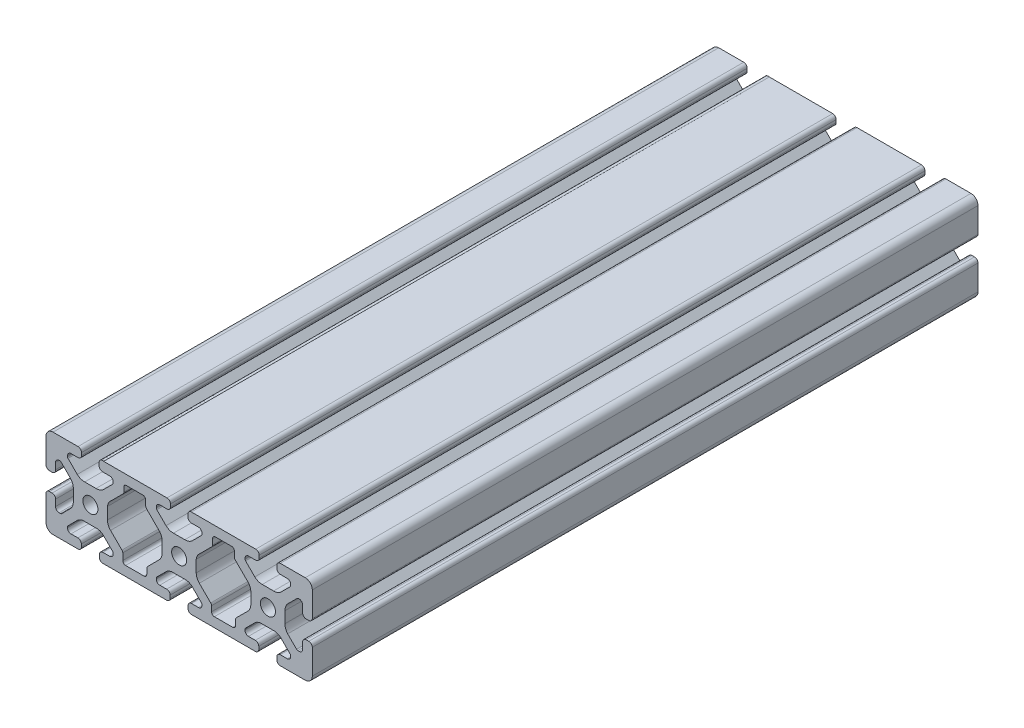
SolidWorks part; units mm, degrees
material "6105-T5 Aluminum"
ref_plane "Front Plane" through (0, 0, 0) normal (0, 0, 1) x (1, 0, 0)
ref_plane "Top Plane" through (0, 0, 0) normal (0, 1, 0) x (1, 0, 0)
ref_plane "Right Plane" through (0, 0, 0) normal (1, 0, 0) x (0, 0, -1)
sketch "Sketch1" plane through (0, 0, 0) normal (0, 0, 1) x (1, 0, 0)
  line L0 (-66.9907, 0) -> (65.4005, 0) construction
  line L128 (-34.0397, 20) -> (-5.4835, 20)
  line L129 (-36.0865, 17.2476) -> (-36.0865, 18.4276)
  line L130 (-31.285, 15.68) -> (-34.5165, 15.68)
  line L131 (-29.715, 13.6545) -> (-29.715, 14.11)
  line L132 (-16.3366, 15.68) -> (-23.6634, 15.68)
  line L133 (-24.9334, 14.9061) -> (-24.9334, 12.538)
  line L134 (-25.3054, 11.6399) -> (-30.5988, 6.3465)
  line L135 (-32.3, 3.2591) -> (-32.3, -2.0252)
  line L136 (-14.009, -20) -> (-21.7801, -20)
  line L137 (-19.7616, 20) -> (-19.7616, -25.1394) construction
  line L138 (-24.1394, -15.68) -> (-15.8606, -15.68)
  line L139 (-25.4094, -11.4093) -> (-25.4094, -14.41)
  line L140 (-30.9088, -5.384) -> (-25.7814, -10.5113)
  line L142 (-29.9376, 13.1171) -> (-34.0919, 8.9628)
  line L143 (-37.4506, 7.7) -> (-42.5494, 7.7)
  line L144 (-45.9081, 8.9628) -> (-50.0624, 13.1171)
  line L145 (-50.285, 13.6545) -> (-50.285, 14.11)
  line L146 (-48.715, 15.68) -> (-45.5696, 15.68)
  line L147 (-43.9996, 17.25) -> (-43.9996, 18.43)
  line L148 (-45.5696, 20) -> (-53, 20)
  line L149 (-53, 20) -> (-56.83, 20)
  line L150 (-60, 16.8406) -> (-60, 13.0106)
  line L151 (-60, 13.0106) -> (-60, 5.5825)
  line L152 (-58.3243, 4.1259) -> (-57.1443, 4.1259)
  line L153 (-55.68, 5.8839) -> (-55.68, 8.7865)
  line L154 (-54.11, 10.3565) -> (-53.726, 10.3565)
  line L155 (-53.1886, 10.1339) -> (-49.0111, 5.9564)
  line L156 (-47.7, 2.571) -> (-47.7, -2.502)
  line L157 (-48.9155, -5.8608) -> (-52.9291, -9.8744)
  line L158 (-53.4665, -10.097) -> (-54.111, -10.097)
  line L159 (-55.68, -8.4722) -> (-55.68, -5.5696)
  line L160 (-57.25, -3.9996) -> (-58.43, -3.9996)
  line L161 (-60, -5.5696) -> (-60, -13)
  line L162 (-60, -13) -> (-60, -16.83)
  line L163 (-57.0574, -20) -> (-53.2274, -20)
  line L164 (-53.2274, -20) -> (-45.797, -20)
  line L165 (-44.06, -18.4389) -> (-44.06, -17.25)
  line L166 (-45.63, -15.68) -> (-48.7404, -15.68)
  line L167 (-50.3104, -14.11) -> (-50.3104, -13.7197)
  line L168 (-50.0878, -13.1823) -> (-46.3105, -9.405)
  line L169 (-43.3425, -7.7407) -> (-36.6594, -7.7407)
  line L170 (-33.6914, -9.405) -> (-29.9611, -13.1353)
  line L171 (-29.7385, -13.6727) -> (-29.7385, -14.1108)
  line L172 (-31.2596, -15.68) -> (-34.37, -15.68)
  line L173 (-35.94, -17.25) -> (-35.94, -18.43)
  line L174 (-34.37, -20) -> (-25.991, -20)
  line L175 (-25.991, -20) -> (-21.7801, -20)
  line L176 (-5.63, -20) -> (-14.009, -20)
  line L177 (-4.06, -17.2093) -> (-4.06, -18.43)
  line L178 (-8.7404, -15.68) -> (-5.63, -15.68)
  line L179 (-10.3104, -13.7197) -> (-10.3104, -14.11)
  line L180 (-6.3105, -9.405) -> (-10.0878, -13.1823)
  line L181 (3.3406, -7.7407) -> (-3.3425, -7.7407)
  line L182 (29.9376, 13.1171) -> (34.0919, 8.9628)
  line L183 (3.9116, 17.25) -> (3.9116, 18.43)
  line L184 (8.715, 15.68) -> (5.4816, 15.68)
  line L185 (10.285, 13.6545) -> (10.285, 14.11)
  line L186 (15.0666, 14.2735) -> (15.0666, 11.9054)
  line L187 (14.6946, 11.0074) -> (9.4012, 5.7139)
  line L188 (7.7, 2.6265) -> (7.7, -2.6578)
  line L189 (14.5906, -12.0419) -> (14.5906, -14.41)
  line L190 (9.0912, -6.0165) -> (14.2186, -11.1439)
  line L191 (10.0624, 13.1171) -> (5.9081, 8.9628)
  line L192 (6.3086, -9.405) -> (10.037, -13.1334)
  line L193 (10.2596, -13.6708) -> (10.2596, -14.11)
  line L194 (8.6896, -15.68) -> (5.5792, -15.68)
  line L195 (4.0092, -17.2093) -> (4.0092, -18.43)
  line L196 (5.5792, -20) -> (13.9582, -20)
  line L197 (25.9402, -20) -> (21.7292, -20)
  line L198 (34.3192, -20) -> (25.9402, -20)
  line L199 (35.8892, -17.2093) -> (35.8892, -18.43)
  line L200 (31.2088, -15.68) -> (34.3192, -15.68)
  line L201 (29.6886, -13.6708) -> (29.6886, -14.0552)
  line L202 (33.6397, -9.405) -> (29.9112, -13.1334)
  line L203 (43.2907, -7.7407) -> (36.6076, -7.7407)
  line L204 (50.036, -13.1823) -> (46.2587, -9.405)
  line L205 (50.2586, -14.0552) -> (50.2586, -13.7197)
  line L206 (45.5792, -15.68) -> (48.6896, -15.68)
  line L207 (-2.5494, 7.7) -> (2.5494, 7.7)
  line L208 (-10.0624, 13.1171) -> (-5.9081, 8.9628)
  line L209 (-9.0912, -6.0165) -> (-14.2186, -11.1439)
  line L210 (-14.5906, -12.0419) -> (-14.5906, -14.41)
  line L211 (-7.7, 2.6265) -> (-7.7, -2.6578)
  line L212 (-14.6946, 11.1439) -> (-9.4012, 5.8505)
  line L213 (-15.0666, 14.41) -> (-15.0666, 12.0419)
  line L214 (-10.285, 13.6545) -> (-10.285, 14.11)
  line L215 (-8.715, 15.68) -> (-5.4835, 15.68)
  line L216 (-3.9135, 17.25) -> (-3.9135, 18.43)
  line L217 (-40, 24.8708) -> (-40, -18.43) construction
  line L218 (0, 29.4355) -> (0, -23.1087) construction
  line L219 (-23.0962, 16.9038) -> (-63.6857, -23.6857) construction
  line L220 (-56.2671, 16.2671) -> (-22.7875, -17.2125) construction
  line L221 (44.0092, -18.4389) -> (44.0092, -17.2093)
  line L222 (53.1766, -20) -> (45.7462, -20)
  line L223 (57.0066, -20) -> (53.1766, -20)
  line L224 (60, -13) -> (60, -16.83)
  line L225 (60, -5.5696) -> (60, -13)
  line L226 (57.25, -3.9996) -> (58.43, -3.9996)
  line L227 (55.68, -8.4722) -> (55.68, -5.5696)
  line L228 (53.4665, -10.097) -> (54.111, -10.097)
  line L229 (48.9155, -5.8608) -> (52.9291, -9.8744)
  line L230 (47.7, 2.571) -> (47.7, -2.502)
  line L231 (53.1886, 10.1339) -> (49.0111, 5.9564)
  line L232 (54.11, 10.3565) -> (53.726, 10.3565)
  line L233 (55.68, 5.8839) -> (55.68, 8.7865)
  line L234 (58.3243, 4.1259) -> (57.1443, 4.1259)
  line L235 (60, 13.0106) -> (60, 5.5825)
  line L236 (60, 16.8406) -> (60, 13.0106)
  line L237 (53, 20) -> (56.83, 20)
  line L238 (45.5696, 20) -> (53, 20)
  line L239 (43.9996, 17.25) -> (43.9996, 18.43)
  line L240 (48.715, 15.68) -> (45.5696, 15.68)
  line L241 (50.285, 13.6545) -> (50.285, 14.11)
  line L242 (45.9081, 8.9628) -> (50.0624, 13.1171)
  line L243 (37.4506, 7.7) -> (42.5494, 7.7)
  line L244 (30.9088, -6.0165) -> (25.7814, -11.1439)
  line L245 (25.4094, -12.0419) -> (25.4094, -14.41)
  line L246 (24.1394, -15.68) -> (15.8606, -15.68)
  line L247 (13.9582, -20) -> (21.7292, -20)
  line L248 (32.3, 2.6265) -> (32.3, -2.6578)
  line L249 (25.3054, 11.1439) -> (30.5988, 5.8505)
  line L250 (24.9334, 14.41) -> (24.9334, 12.0419)
  line L251 (16.3366, 15.68) -> (23.6634, 15.68)
  line L252 (29.715, 13.6545) -> (29.715, 14.11)
  line L253 (31.285, 15.68) -> (34.5165, 15.68)
  line L254 (36.0865, 17.25) -> (36.0865, 18.43)
  line L255 (34.5165, 20) -> (5.4816, 20)
  arc A111 (-36.0865, 18.4276) -> (-34.0397, 20) centre (-34.5184, 18.5048) cw
  circle A112 centre (-40, 0) radius 3.4
  arc A113 (-34.5165, 15.68) -> (-36.0865, 17.2476) centre (-34.5165, 17.25) cw
  arc A114 (-31.285, 15.68) -> (-29.715, 14.11) centre (-31.285, 14.11) cw
  arc A115 (-29.715, 13.6545) -> (-29.9376, 13.1171) centre (-30.475, 13.6545) cw
  arc A116 (-32.3, -2.0252) -> (-30.9088, -5.384) centre (-27.55, -2.0252) ccw
  arc A117 (-23.6634, 15.68) -> (-24.9334, 14.9061) centre (-23.7626, 14.4139) ccw
  arc A118 (-25.3054, 11.6399) -> (-24.9334, 12.538) centre (-26.2034, 12.538) ccw
  arc A119 (-30.5988, 6.3465) -> (-32.3, 3.2591) centre (-27.5862, 2.6741) ccw
  arc A120 (-25.4094, -14.41) -> (-24.1394, -15.68) centre (-24.1394, -14.41) ccw
  arc A121 (-25.4094, -11.4093) -> (-25.7814, -10.5113) centre (-26.6794, -11.4093) ccw
  arc A122 (-37.4506, 7.7) -> (-34.0919, 8.9628) centre (-37.3191, 12.4482) ccw
  arc A123 (-45.9081, 8.9628) -> (-42.5494, 7.7) centre (-42.6809, 12.4482) ccw
  arc A124 (-50.285, 13.6545) -> (-50.0624, 13.1171) centre (-49.525, 13.6545) ccw
  arc A125 (-48.715, 15.68) -> (-50.285, 14.11) centre (-48.715, 14.11) ccw
  arc A126 (-45.5696, 15.68) -> (-43.9996, 17.25) centre (-45.5696, 17.25) ccw
  arc A127 (-43.9996, 18.43) -> (-45.5696, 20) centre (-45.5696, 18.43) ccw
  arc A128 (-56.83, 20) -> (-60, 16.8406) centre (-56.83, 16.83) ccw
  arc A129 (-60, 5.5825) -> (-58.3243, 4.1259) centre (-58.4338, 5.692) ccw
  arc A130 (-57.1443, 4.1259) -> (-55.68, 5.8839) centre (-57.2384, 5.693) ccw
  arc A131 (-54.11, 10.3565) -> (-55.68, 8.7865) centre (-54.11, 8.7865) ccw
  arc A132 (-53.1886, 10.1339) -> (-53.726, 10.3565) centre (-53.726, 9.5965) ccw
  arc A133 (-47.7, 2.571) -> (-49.0111, 5.9564) centre (-52.4488, 2.6785) ccw
  arc A134 (-48.9155, -5.8608) -> (-47.7, -2.502) centre (-52.4465, -2.6836) ccw
  arc A135 (-53.4665, -10.097) -> (-52.9291, -9.8744) centre (-53.4665, -9.337) ccw
  arc A136 (-55.68, -8.4722) -> (-54.111, -10.097) centre (-54.111, -8.527) ccw
  arc A137 (-55.68, -5.5696) -> (-57.25, -3.9996) centre (-57.25, -5.5696) ccw
  arc A138 (-58.43, -3.9996) -> (-60, -5.5696) centre (-58.43, -5.5696) ccw
  arc A139 (-60, -16.83) -> (-57.0574, -20) centre (-56.83, -16.8382) ccw
  arc A140 (-45.797, -20) -> (-44.06, -18.4389) centre (-45.63, -18.4389) ccw
  arc A141 (-44.06, -17.25) -> (-45.63, -15.68) centre (-45.63, -17.25) ccw
  arc A142 (-50.3104, -14.11) -> (-48.7404, -15.68) centre (-48.7404, -14.11) ccw
  arc A143 (-50.0878, -13.1823) -> (-50.3104, -13.7197) centre (-49.5504, -13.7197) ccw
  arc A144 (-43.3425, -7.7407) -> (-46.3105, -9.405) centre (-42.6575, -12.4411) ccw
  arc A145 (-33.6914, -9.405) -> (-36.6594, -7.7407) centre (-37.3444, -12.4411) ccw
  arc A146 (-29.7385, -13.6727) -> (-29.9611, -13.1353) centre (-30.4985, -13.6727) ccw
  arc A147 (-31.2596, -15.68) -> (-29.7385, -14.1108) centre (-31.3085, -14.1108) ccw
  arc A148 (-34.37, -15.68) -> (-35.94, -17.25) centre (-34.37, -17.25) ccw
  arc A149 (-35.94, -18.43) -> (-34.37, -20) centre (-34.37, -18.43) ccw
  arc A150 (-4.06, -18.43) -> (-5.63, -20) centre (-5.63, -18.43) cw
  arc A151 (-5.63, -15.68) -> (-4.06, -17.2093) centre (-5.6295, -17.25) cw
  arc A152 (-8.7404, -15.68) -> (-10.3104, -14.11) centre (-8.7404, -14.11) cw
  arc A153 (-10.3104, -13.7197) -> (-10.0878, -13.1823) centre (-9.5504, -13.7197) cw
  arc A154 (-6.3105, -9.405) -> (-3.3425, -7.7407) centre (-2.6575, -12.4411) cw
  arc A155 (3.9116, 18.43) -> (5.4816, 20) centre (5.4816, 18.43) cw
  arc A156 (5.4816, 15.68) -> (3.9116, 17.25) centre (5.4816, 17.25) cw
  arc A157 (8.715, 15.68) -> (10.285, 14.11) centre (8.715, 14.11) cw
  arc A158 (10.285, 13.6545) -> (10.0624, 13.1171) centre (9.525, 13.6545) cw
  arc A159 (7.7, -2.6578) -> (9.0912, -6.0165) centre (12.45, -2.6578) ccw
  arc A160 (16.3366, 15.68) -> (15.0666, 14.2735) centre (16.3292, 14.41) ccw
  arc A161 (14.6946, 11.0074) -> (15.0666, 11.9054) centre (13.7966, 11.9054) ccw
  arc A162 (9.4012, 5.7139) -> (7.7, 2.6265) centre (12.4138, 2.0415) ccw
  arc A163 (14.5906, -14.41) -> (15.8606, -15.68) centre (15.8606, -14.41) ccw
  arc A164 (14.5906, -12.0419) -> (14.2186, -11.1439) centre (13.3206, -12.0419) ccw
  arc A165 (2.5494, 7.7) -> (5.9081, 8.9628) centre (2.6809, 12.4482) ccw
  arc A166 (6.3086, -9.405) -> (3.3406, -7.7407) centre (2.6556, -12.4411) ccw
  arc A167 (10.2596, -13.6708) -> (10.037, -13.1334) centre (9.4996, -13.6708) ccw
  arc A168 (8.6896, -15.68) -> (10.2596, -14.11) centre (8.6896, -14.11) ccw
  arc A169 (5.5792, -15.68) -> (4.0092, -17.2093) centre (5.5787, -17.25) ccw
  arc A170 (4.0092, -18.43) -> (5.5792, -20) centre (5.5792, -18.43) ccw
  arc A171 (35.8892, -18.43) -> (34.3192, -20) centre (34.3192, -18.43) cw
  arc A172 (34.3192, -15.68) -> (35.8892, -17.2093) centre (34.3197, -17.25) cw
  arc A173 (31.2088, -15.68) -> (29.6886, -14.0552) centre (31.2577, -14.1108) cw
  arc A174 (29.6886, -13.6708) -> (29.9112, -13.1334) centre (30.4486, -13.6708) cw
  arc A175 (33.6397, -9.405) -> (36.6076, -7.7407) centre (37.2927, -12.4411) cw
  arc A176 (43.2907, -7.7407) -> (46.2587, -9.405) centre (42.6057, -12.4411) cw
  arc A177 (-2.5494, 7.7) -> (-5.9081, 8.9628) centre (-2.6809, 12.4482) cw
  arc A178 (-14.5906, -12.0419) -> (-14.2186, -11.1439) centre (-13.3206, -12.0419) cw
  arc A179 (-14.5906, -14.41) -> (-15.8606, -15.68) centre (-15.8606, -14.41) cw
  arc A180 (-9.4012, 5.8505) -> (-7.7, 2.6265) centre (-12.43, 2.1914) cw
  arc A181 (-14.6946, 11.1439) -> (-15.0666, 12.0419) centre (-13.7966, 12.0419) cw
  arc A182 (-16.3366, 15.68) -> (-15.0666, 14.41) centre (-16.3366, 14.41) cw
  arc A183 (-7.7, -2.6578) -> (-9.0912, -6.0165) centre (-12.45, -2.6578) cw
  arc A184 (-10.285, 13.6545) -> (-10.0624, 13.1171) centre (-9.525, 13.6545) ccw
  arc A185 (-8.715, 15.68) -> (-10.285, 14.11) centre (-8.715, 14.11) ccw
  arc A186 (-5.4835, 15.68) -> (-3.9135, 17.25) centre (-5.4835, 17.25) ccw
  circle A187 centre (0, 0) radius 3.4
  arc A188 (-3.9135, 18.43) -> (-5.4835, 20) centre (-5.4835, 18.43) ccw
  arc A189 (50.036, -13.1823) -> (50.2586, -13.7197) centre (49.4986, -13.7197) cw
  arc A190 (50.2586, -14.0552) -> (48.6896, -15.68) centre (48.6896, -14.11) cw
  arc A191 (44.0092, -17.2093) -> (45.5792, -15.68) centre (45.5787, -17.25) cw
  arc A192 (45.7462, -20) -> (44.0092, -18.4389) centre (45.5792, -18.4389) cw
  arc A193 (60, -16.83) -> (57.0066, -20) centre (56.83, -16.8349) cw
  arc A194 (58.43, -3.9996) -> (60, -5.5696) centre (58.43, -5.5696) cw
  arc A195 (55.68, -5.5696) -> (57.25, -3.9996) centre (57.25, -5.5696) cw
  arc A196 (55.68, -8.4722) -> (54.111, -10.097) centre (54.111, -8.527) cw
  arc A197 (53.4665, -10.097) -> (52.9291, -9.8744) centre (53.4665, -9.337) cw
  arc A198 (48.9155, -5.8608) -> (47.7, -2.502) centre (52.4465, -2.6836) cw
  arc A199 (47.7, 2.571) -> (49.0111, 5.9564) centre (52.4488, 2.6785) cw
  arc A200 (53.1886, 10.1339) -> (53.726, 10.3565) centre (53.726, 9.5965) cw
  arc A201 (54.11, 10.3565) -> (55.68, 8.7865) centre (54.11, 8.7865) cw
  arc A202 (57.1443, 4.1259) -> (55.68, 5.8839) centre (57.2384, 5.693) cw
  arc A203 (60, 5.5825) -> (58.3243, 4.1259) centre (58.4338, 5.692) cw
  arc A204 (56.83, 20) -> (60, 16.8406) centre (56.83, 16.83) cw
  arc A205 (43.9996, 18.43) -> (45.5696, 20) centre (45.5696, 18.43) cw
  arc A206 (45.5696, 15.68) -> (43.9996, 17.25) centre (45.5696, 17.25) cw
  arc A207 (48.715, 15.68) -> (50.285, 14.11) centre (48.715, 14.11) cw
  arc A208 (50.285, 13.6545) -> (50.0624, 13.1171) centre (49.525, 13.6545) cw
  arc A209 (45.9081, 8.9628) -> (42.5494, 7.7) centre (42.6809, 12.4482) cw
  arc A210 (37.4506, 7.7) -> (34.0919, 8.9628) centre (37.3191, 12.4482) cw
  arc A211 (25.4094, -12.0419) -> (25.7814, -11.1439) centre (26.6794, -12.0419) cw
  arc A212 (25.4094, -14.41) -> (24.1394, -15.68) centre (24.1394, -14.41) cw
  arc A213 (30.5988, 5.8505) -> (32.3, 2.6265) centre (27.57, 2.1914) cw
  arc A214 (25.3054, 11.1439) -> (24.9334, 12.0419) centre (26.2034, 12.0419) cw
  arc A215 (23.6634, 15.68) -> (24.9334, 14.41) centre (23.6634, 14.41) cw
  arc A216 (32.3, -2.6578) -> (30.9088, -6.0165) centre (27.55, -2.6578) cw
  arc A217 (29.715, 13.6545) -> (29.9376, 13.1171) centre (30.475, 13.6545) ccw
  arc A218 (31.285, 15.68) -> (29.715, 14.11) centre (31.285, 14.11) ccw
  arc A219 (34.5165, 15.68) -> (36.0865, 17.25) centre (34.5165, 17.25) ccw
  circle A220 centre (40, 0) radius 3.4
  arc A221 (36.0865, 18.43) -> (34.5165, 20) centre (34.5165, 18.43) ccw
  dimension "D4" = 12.3
  dimension "D11" = 6.8
  dimension "D1" = 40
  dimension "D2" = 40
  dimension "D3" = 120
  dimension "D5" = 20.57
  dimension "D6" = 4.32
  dimension "D7" = 4.32
  dimension "D8" = 4.32
  dimension "D9" = 12.3
  dimension "D10" = 20
  dimension "D12" = 8.12
  dimension "D13" = 4.32
  dimension "D14" = 4.32
extrude "Extrude1" add sketch "Sketch1" against normal blind 300
